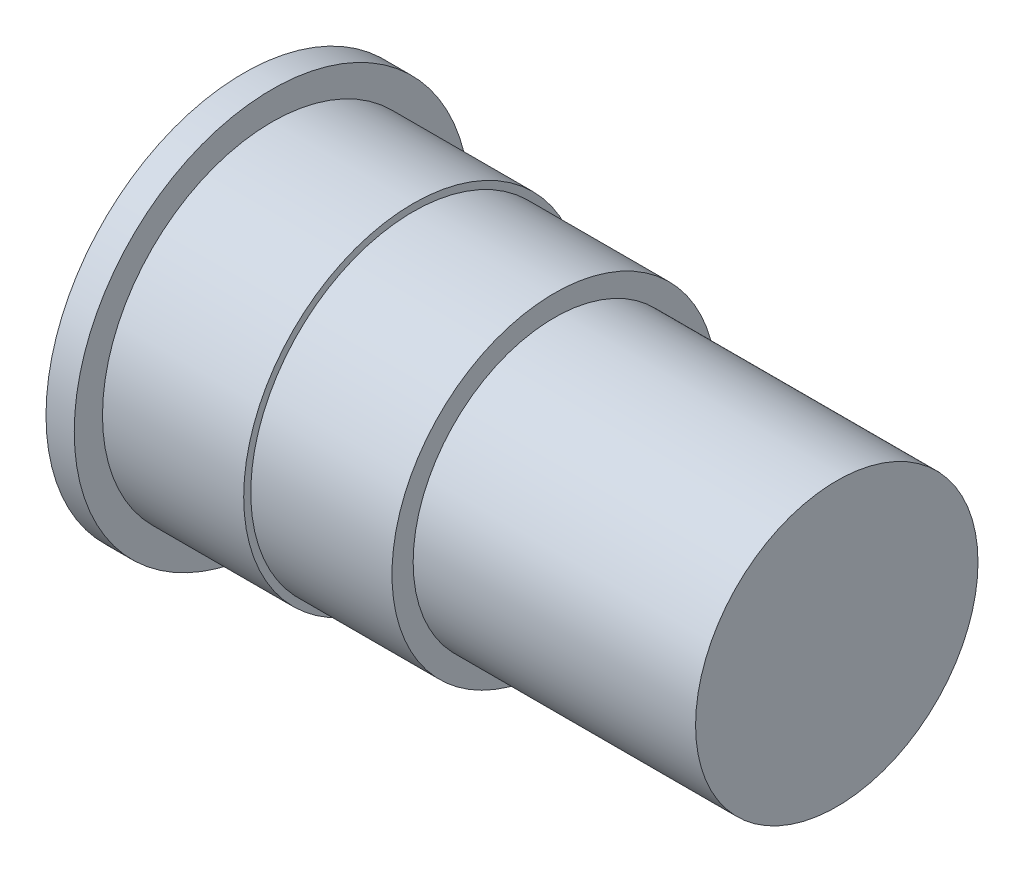
SolidWorks part; units mm, degrees
material "6061 合金"
ref_plane "前视基准面" through (0, 0, 0) normal (0, 0, 1) x (1, 0, 0)
ref_plane "上视基准面" through (0, 0, 0) normal (0, 1, 0) x (1, 0, 0)
ref_plane "右视基准面" through (0, 0, 0) normal (1, 0, 0) x (0, 0, -1)
sketch "草图1" plane through (0, 0, 0) normal (1, 0, 0) x (0, 0, -1)
  circle A0 centre (0, 0) radius 7
  dimension "D1" = 14
extrude "凸台-拉伸1" add sketch "草图1" along normal blind 1
sketch "草图2" plane through (1, 0, 0) normal (1, 0, 0) x (0, 0, -1)
  circle A0 centre (0, 0) radius 6
  dimension "D1" = 12
extrude "凸台-拉伸2" add sketch "草图2" along normal blind 5
sketch "草图3" plane through (6, 0, 0) normal (1, 0, 0) x (0, 0, -1)
  circle A0 centre (0, 0) radius 5.75
  dimension "D1" = 11.5
extrude "凸台-拉伸3" add sketch "草图3" along normal blind 5
sketch "草图4" plane through (11, 0, 0) normal (1, 0, 0) x (0, 0, -1)
  circle A0 centre (0, 0) radius 5
  dimension "D1" = 10
extrude "凸台-拉伸4" add sketch "草图4" along normal blind 10
sketch "草图5" plane through (0, 0, 0) normal (0, 1, 0) x (1, 0, 0)
  line L0 (0, 0) -> (95, 0) construction
  dimension "D1" = 95
